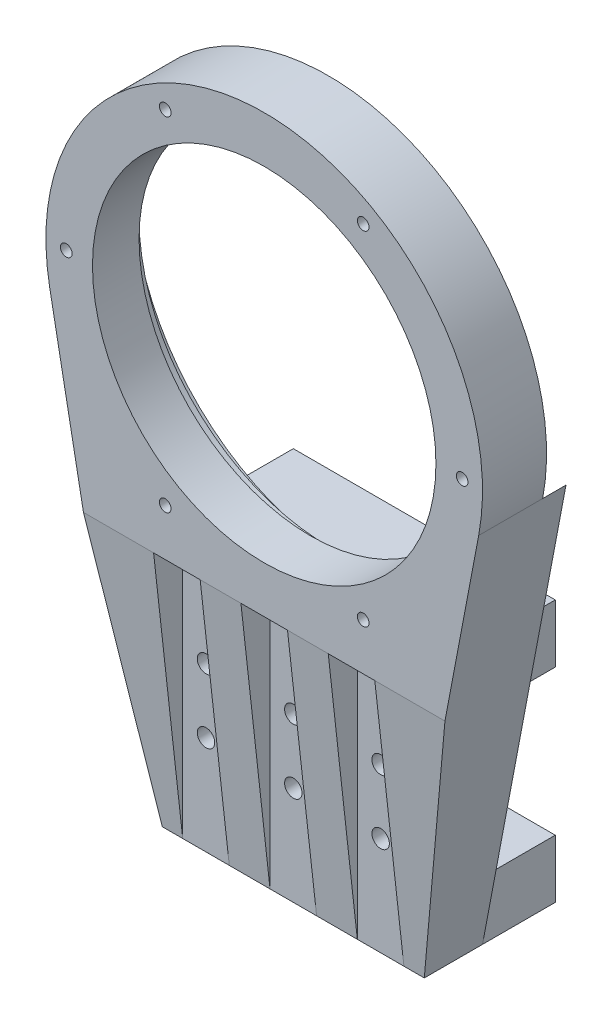
SolidWorks part; units mm, degrees
material "ABS"
ref_plane "Front Plane" through (0, 0, 0) normal (0, 0, 1) x (1, 0, 0)
ref_plane "Top Plane" through (0, 0, 0) normal (0, 1, 0) x (1, 0, 0)
ref_plane "Right Plane" through (0, 0, 0) normal (1, 0, 0) x (0, 0, -1)
sketch "Sketch1" plane through (0, 0, 0) normal (0, 0, 1) x (1, 0, 0)
  line L0 (0, 0) -> (0, -75.7544) construction
  line L1 (-22.5, -82.5) -> (22.5, -82.5)
  line L4 (22.5, -82.5) -> (36.8413, -6.9978)
  line L5 (-22.5, -82.5) -> (-36.8413, -6.9978)
  circle A0 centre (0, 0) radius 29.5
  circle A1 centre (0, 0) radius 37.5
  arc A2 (-22.5, -30) -> (6.0194, -37.0137) centre (0, 0) ccw
  arc A3 (37.5, 0) -> (6.0194, -37.0137) centre (0, 0) cw
  arc A4 (-36.8413, -6.9978) -> (-22.5, -30) centre (0, 0) ccw
  arc A5 (6.0194, -37.0137) -> (-5.2342, -37.1329) centre (0, 0) ccw
  arc A6 (-22.5, -30) -> (-36.8413, -6.9978) centre (0, 0) cw
  arc A7 (6.0194, -37.0137) -> (-5.2342, -37.1329) centre (0, 0) ccw
  arc A8 (36.8413, -6.9978) -> (-36.8413, -6.9978) centre (0, 0) cw
  dimension "D1" = 45
  dimension "D2" = 75
  dimension "D3" = 59
  dimension "D4" = 82.5
extrude "Boss-Extrude1" add sketch "Sketch1" along normal blind 15
sketch "Sketch2" plane through (0, 0, 0) normal (0, 0, -1) x (-1, 0, 0)
  circle A0 centre (0, 0) radius 32.5
  circle A1 centre (0, 0) radius 27.5
extrude "Cut-Extrude1" cut sketch "Sketch2" against normal blind 7
sketch "Sketch7" plane through (0, 0, 0) normal (0, 0, -1) x (-1, 0, 0)
  line L0 (-22.5, -82.5) -> (-22.5, -72.5)
  line L13 (22.5, -82.5) -> (22.5, -72.5)
  line L18 (22.5, -72.5) -> (-22.5, -72.5)
  line L19 (-22.5, -47.5) -> (-22.5, -37.5)
  line L20 (-22.5, -37.5) -> (22.5, -37.5)
  line L21 (-22.5, -82.5) -> (22.5, -82.5)
  line L31 (22.5, -37.5) -> (22.5, -47.5)
  line L32 (22.5, -47.5) -> (-22.5, -47.5)
  dimension "D1" = 25
  dimension "D2" = 10
  dimension "D3" = 10
sketch "Sketch9" plane through (0, 0, 15) normal (0, 0, 1) x (1, 0, 0)
  line L0 (60.1553, 0) -> (-60.1553, 0) construction
  line L1 (-60.1553, 0) -> (0, 0) construction
  line L2 (0, 0) -> (27.4803, 47.5973) construction
  line L3 (27.4803, 47.5973) -> (-28.626, -49.5817) construction
  line L4 (-28.626, -49.5817) -> (0, 0) construction
  line L5 (-29.2217, 50.6135) -> (0, 0) construction
  line L6 (0, 0) -> (29.2328, -50.6327) construction
  circle A0 centre (0, 0) radius 34 construction
  circle A1 centre (17, 29.4449) radius 1
  circle A2 centre (34, 0) radius 1
  circle A3 centre (17, -29.4449) radius 1
  circle A4 centre (-17, -29.4449) radius 1
  circle A5 centre (-34, 0) radius 1
  circle A6 centre (-17, 29.4449) radius 1
  dimension "D1" = 60
  dimension "D2" = 60
extrude "Cut-Extrude5" cut sketch "Sketch9" against normal blind 15
sketch "Sketch10" plane through (0, 0, 0) normal (0, 0, -1) x (-1, 0, 0)
  circle A0 centre (0, 0) radius 37.5
extrude "Cut-Extrude6" cut sketch "Sketch10" against normal blind 4
extrude "Boss-Extrude3" add sketch "Sketch7" along normal blind 12.5
sketch "Sketch12" plane through (0, 0, 0) normal (0, 0, -1) x (-1, 0, 0)
  line L3 (0, 53.5172) -> (0, -108.1009) construction
  circle A0 centre (-15, -54.5) radius 1.5
  circle A1 centre (0, -54.5) radius 1.5
  circle A2 centre (15, -54.5) radius 1.5
  circle A3 centre (-15, -65.5) radius 1.5
  circle A4 centre (0, -65.5) radius 1.5
  circle A5 centre (15, -65.5) radius 1.5
  dimension "D1" = 3
  dimension "D2" = 15
  dimension "D3" = 11
  dimension "D4" = 11
  dimension "D5" = 11
  dimension "D8" = 0
  dimension "D9" = 0
  dimension "D10" = 15
  dimension "D12" = 15
  dimension "D13" = 15
extrude "Cut-Extrude8" cut sketch "Sketch12" against normal blind 15
sketch "Sketch13" plane through (0, 0, 0) normal (1, 0, 0) x (0, 0, -1)
  line L0 (-15, -82.5) -> (-15, -37.5)
  line L1 (-15, -82.5) -> (-15, -6.9978) construction
  line L2 (-15, -37.5) -> (-10, -82.5)
  line L3 (-15, -82.5) -> (0, -82.5) construction
  line L4 (-10, -82.5) -> (-15, -82.5)
  dimension "D1" = 45
  dimension "D2" = 5
extrude "Cut-Extrude9" cut sketch "Sketch13" against normal blind 35 and the other way blind 35
sketch "Sketch14" plane through (0, 0, 15) normal (0, 0, 1) x (1, 0, 0)
  line L0 (31.0475, -37.5) -> (-31.0475, -37.5) construction
  line L1 (-19, -37.5) -> (-11, -37.5)
  line L2 (-19, -37.5) -> (-19, -82.4969)
  line L3 (-19, -82.4969) -> (-11, -82.4969)
  line L4 (-11, -37.5) -> (-11, -82.4969)
  line L5 (0, 57.0113) -> (0, -113.113) construction
  line L6 (11, -37.5) -> (19, -37.5)
  line L7 (11, -37.5) -> (11, -82.4969)
  line L8 (11, -82.4969) -> (19, -82.4969)
  line L9 (19, -37.5) -> (19, -82.4969)
  line L10 (-4, -37.5) -> (4, -37.5)
  line L11 (-4, -37.5) -> (-4, -82.4969)
  line L12 (-4, -82.4969) -> (4, -82.4969)
  line L13 (4, -37.5) -> (4, -82.4969)
  dimension "D1" = 8
  dimension "D2" = 8
  dimension "D3" = 8
  dimension "D4" = 4
  dimension "D5" = 11
  dimension "D6" = 11
extrude "Cut-Extrude10" cut sketch "Sketch14" against normal blind 5
